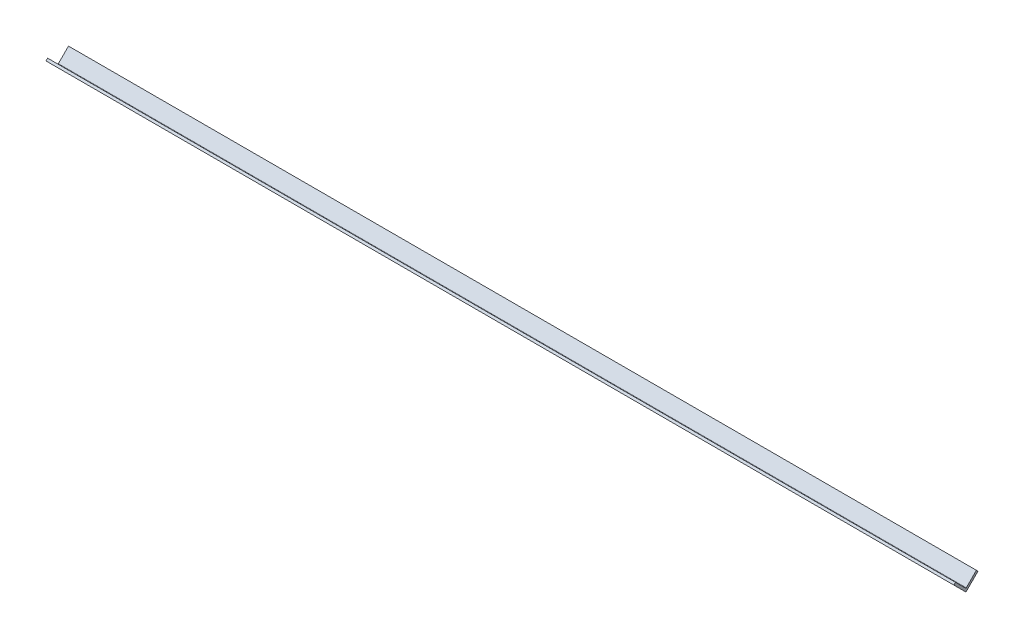
SolidWorks part; units mm, degrees
ref_plane "Front Plane" through (0, 0, 0) normal (0, 0, 1) x (1, 0, 0)
ref_plane "Top Plane" through (0, 0, 0) normal (0, 1, 0) x (1, 0, 0)
ref_plane "Right Plane" through (0, 0, 0) normal (1, 0, 0) x (0, 0, -1)
sketch "Sketch1" plane through (0, 0, 0) normal (1, 0, 0) x (0, 0, -1)
  line L0 (0.3536, 0.3536) -> (13.435, 13.435)
  line L1 (13.435, 13.435) -> (11.639, 15.2311)
  line L2 (11.639, 15.2311) -> (0.3536, 3.9457)
  line L3 (0, 0) -> (0, 21.9334) construction
  line L4 (-0.3536, 0.3536) -> (-13.435, 13.435)
  line L5 (-13.435, 13.435) -> (-11.639, 15.2311)
  line L6 (-11.639, 15.2311) -> (-0.3536, 3.9457)
  arc A0 (-0.3536, 3.9457) -> (0.3536, 3.9457) centre (0, 4.2992) ccw
  arc A1 (-0.3536, 0.3536) -> (0.3536, 0.3536) centre (0, 0.7071) ccw
  point P10 (0, 3.5921)
  dimension "D4" = 0.5
  dimension "D1" = 2.54
  dimension "D2" = 19
  dimension "D3" = 45
extrude "Boss-Extrude1" add sketch "Sketch1" along normal blind 1012
